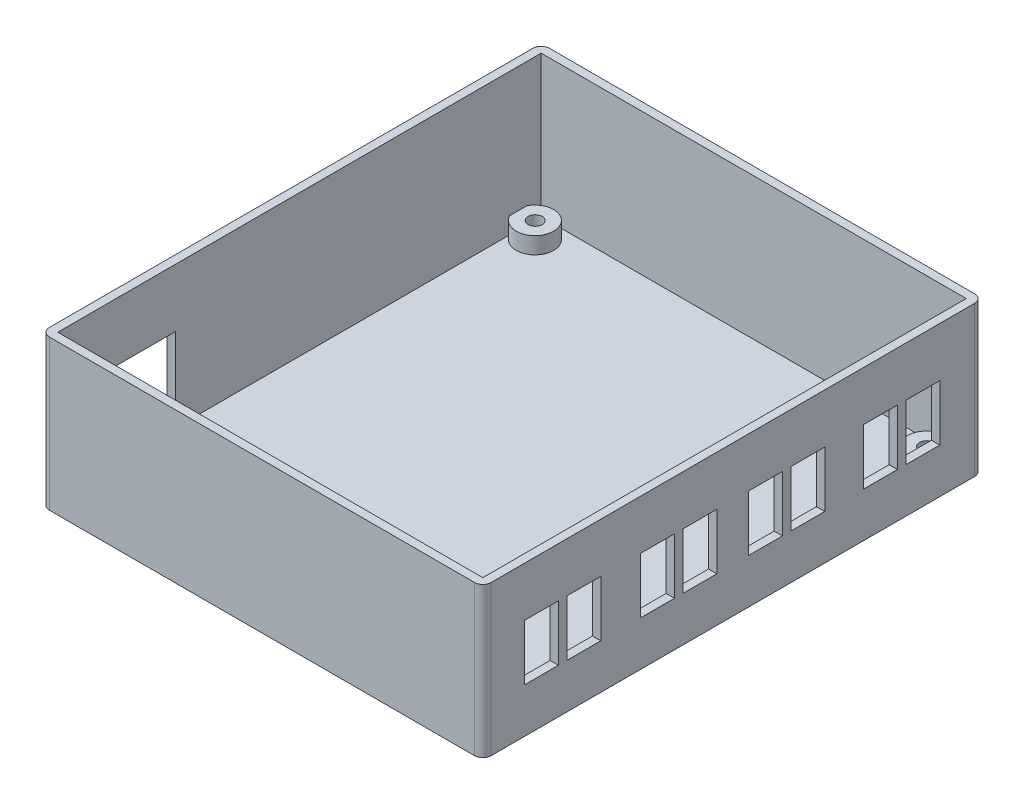
SolidWorks part; units mm, degrees
ref_plane "Ebene vorne" through (0, 0, 0) normal (0, 0, 1) x (1, 0, 0)
ref_plane "Ebene oben" through (0, 0, 0) normal (0, 1, 0) x (1, 0, 0)
ref_plane "Ebene rechts" through (0, 0, 0) normal (1, 0, 0) x (0, 0, -1)
sketch "Skizze1" plane through (0, 0, 0) normal (0, 1, 0) x (1, 0, 0)
  line L1 (0, 0) -> (106, 0)
  line L2 (0, 0) -> (0, 120)
  line L3 (0, 120) -> (106, 120)
  line L4 (106, 0) -> (106, 120)
  dimension "D1" = 106
  dimension "D2" = 120
extrude "Aufsatz-Linear austragen1" add sketch "Skizze1" along normal blind 36
shell "Wandung1" thickness 2
sketch "Skizze2" plane through (0, 2, 0) normal (0, 1, 0) x (1, 0, 0)
  line L1 (6, 7.5) -> (99.94, 7.5) construction
  line L2 (6, 7.5) -> (6, 112.5) construction
  line L3 (6, 112.5) -> (99.94, 112.5) construction
  line L4 (99.94, 7.5) -> (99.94, 112.5) construction
  line L6 (2, 118) -> (2, 2) construction
  line L7 (2, 2) -> (104, 2) construction
  circle A0 centre (6, 7.5) radius 4.5
  circle A1 centre (99.94, 7.5) radius 4.5
  circle A2 centre (99.94, 112.5) radius 4.5
  circle A3 centre (6, 112.5) radius 4.5
  dimension "D5" = 9
  dimension "D1" = 105
  dimension "D2" = 93.94
  dimension "D3" = 4
  dimension "D4" = 5.5
  dimension "D6" = 2
  dimension "D7" = 2
extrude "Aufsatz-Linear austragen2" add sketch "Skizze2" along normal blind 4
fillet "Verrundung1" radius 2 4 edges at (0, 18, -120) (106, 18, -120) (106, 18, 0) (0, 18, 0)
hole_wizard "Stirnsenkung für M3 Zylinderschraube mit Innensechskant1" positions "Skizze5" profile "Skizze6" counterbore size "M3" standard "DIN"
sketch "Skizze5" plane through (0, 0, 0) normal (0, -1, 0) x (-1, 0, 0)
  line L1 (-100, 7.5) -> (-6.06, 7.5) construction
  line L2 (-100, 7.5) -> (-100, 112.5) construction
  line L3 (-100, 112.5) -> (-6.06, 112.5) construction
  line L4 (-6.06, 7.5) -> (-6.06, 112.5) construction
  line L5 (-2, 0) -> (-104, 0) construction
  line L6 (-106, 2) -> (-106, 118) construction
  point P0 (-100, 7.5)
  point P1 (-6.06, 112.5)
  point P100 (-100, 112.5)
  point P101 (-6.06, 7.5)
  dimension "D1" = 93.94
  dimension "D2" = 105
  dimension "D3" = 7.5
  dimension "D4" = 6
sketch "Skizze6" plane through (100, 0, -7.5) normal (1, 0, 0) x (0, 0, -1)
  line L0 (0, 0) -> (0, 15.0215)
  line L1 (0, 15.0215) -> (1.7, 14)
  line L2 (1.7, 14) -> (1.7, 3.4)
  line L3 (1.7, 3.4) -> (3.25, 3.4)
  line L5 (3.25, 3.4) -> (3.25, 0.025)
  line L6 (3.25, 0.025) -> (3.275, 0)
  line L7 (3.275, 0) -> (0, 0)
  line L8 (-3.25, 0.025) -> (-3.275, 0) construction
  line L10 (0, 15.0215) -> (-1.7, 14) construction
  line L11 (0, -6.35) -> (0, 107.95) construction
  dimension "Bohrerdurchmesser" = 3.4
  dimension "Bohrungstiefe" = 14
  dimension "Senkdurchmesser2" = 6.5
  dimension "Senktiefe2" = 3.4
  dimension "Senkdurchmesser4 (Oben)" = 6.55
  dimension "Senkwinkel2 (Oben)" = 90
  dimension "Spitzenwinkel" = 118
sketch "Skizze7" plane through (0, 0, 0) normal (-1, 0, 0) x (0, 0, 1)
  line L0 (0, 36) -> (0, 0) construction
  line L1 (-30.25, 22.02) -> (-13.25, 22.02)
  line L2 (-30.25, 22.02) -> (-30.25, 7.42)
  line L3 (-30.25, 7.42) -> (-13.25, 7.42)
  line L4 (-13.25, 22.02) -> (-13.25, 7.42)
  line L5 (-30.25, 22.02) -> (-13.25, 7.42) construction
  line L6 (-30.25, 7.42) -> (-13.25, 22.02) construction
  line L7 (-118, 0) -> (-2, 0) construction
  point P0 (-21.75, 14.72)
  dimension "D1" = 17
  dimension "D2" = 14.6
  dimension "D3" = 13.25
  dimension "D4" = 7.42
extrude "Schnitt-Linear austragen1" cut sketch "Skizze7" against normal blind 10
sketch "Skizze8" plane through (106, 0, 0) normal (1, 0, 0) x (0, 0, -1)
  line L0 (2, 0) -> (118, 0) construction
  line L1 (9.98, 24.12) -> (18.14, 24.12)
  line L2 (9.98, 24.12) -> (9.98, 10.72)
  line L3 (9.98, 10.72) -> (18.14, 10.72)
  line L4 (18.14, 24.12) -> (18.14, 10.72)
  line L5 (9.98, 24.12) -> (18.14, 10.72) construction
  line L6 (9.98, 10.72) -> (18.14, 24.12) construction
  line L7 (0, 0) -> (0, 36) construction
  line L9 (20.14, 10.72) -> (28.3, 10.72)
  line L10 (20.14, 10.72) -> (20.14, 24.12)
  line L11 (20.14, 24.12) -> (28.3, 24.12)
  line L12 (28.3, 10.72) -> (28.3, 24.12)
  line L13 (20.14, 10.72) -> (28.3, 24.12) construction
  line L14 (20.14, 24.12) -> (28.3, 10.72) construction
  point P0 (14.06, 17.42)
  point P9 (24.22, 17.42)
  dimension "D1" = 8.16
  dimension "D2" = 13.4
  dimension "D3" = 10.72
  dimension "D4" = 9.98
  dimension "D5" = 2
  dimension "D6" = 8.16
  dimension "D7" = 13.4
  dimension "D8" = 10.72
extrude "Schnitt-Linear austragen2" cut sketch "Skizze8" against normal blind 10
pattern_linear "Lineares Muster2" count 2 spacing 27.85 along (0, 0, -1) of "Schnitt-Linear austragen2"
pattern_linear "Lineares Muster3" count 2 spacing 53.76 along (0, 0, -1) of "Schnitt-Linear austragen2"
pattern_linear "Lineares Muster4" count 2 spacing 81.35 along (0, 0, -1) of "Schnitt-Linear austragen2"
sketch "Skizze10" plane through (0, 0, 0) normal (-1, 0, 0) x (0, 0, 1)
  line L0 (-30.25, 7.42) -> (-13.25, 7.42) construction
  line L1 (-24.25, 7.42) -> (-19.25, 7.42)
  line L2 (-24.25, 7.42) -> (-24.25, 4.42)
  line L3 (-24.25, 4.42) -> (-19.25, 4.42)
  line L4 (-19.25, 7.42) -> (-19.25, 4.42)
  line L5 (-21.75, 22.02) -> (-21.75, -1.3026) construction
  line L6 (-13.25, 22.02) -> (-30.25, 22.02) construction
  dimension "D1" = 5
  dimension "D2" = 3
extrude "Schnitt-Linear austragen3" cut sketch "Skizze10" against normal blind 3
